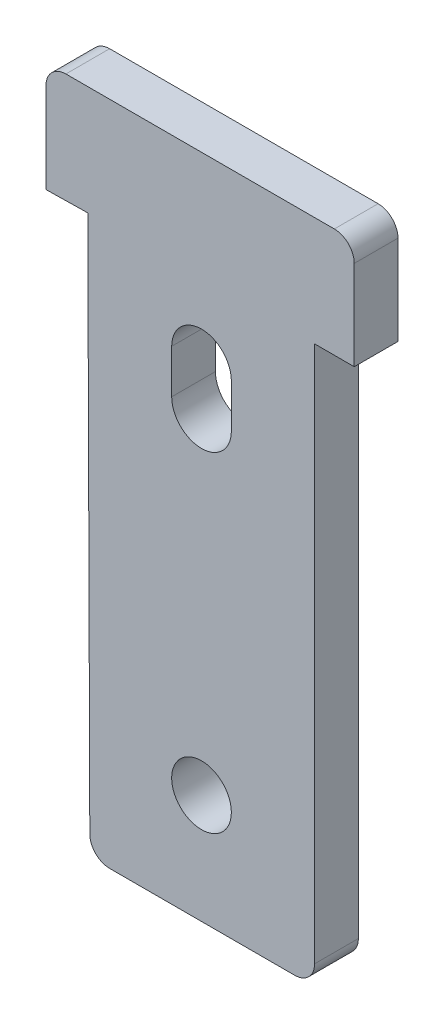
SolidWorks part; units mm, degrees
ref_plane "Front Plane" through (0, 0, 0) normal (0, 0, 1) x (1, 0, 0)
ref_plane "Top Plane" through (0, 0, 0) normal (0, 1, 0) x (1, 0, 0)
ref_plane "Right Plane" through (0, 0, 0) normal (1, 0, 0) x (0, 0, -1)
sketch "Sketch1" plane through (0, 0, 0) normal (0, 0, 1) x (1, 0, 0)
  line L12 (-4.5474, -16.75) -> (4.7563, -16.75)
  line L14 (-7.75, 11.2136) -> (-7.75, 15.75)
  line L17 (0.0702, -16.4445) -> (0.0702, 24.1035) construction
  line L19 (6.75, 16.75) -> (-6.75, 16.75)
  line L24 (0.0702, 5.35) -> (0.0702, 7.55) construction
  line L25 (-1.4298, 5.35) -> (-1.4298, 7.55)
  line L26 (-7.75, 11.2136) -> (-5.65, 11.25)
  line L27 (-5.65, 11.25) -> (-5.5474, -15.7538)
  line L28 (5.7563, -15.75) -> (5.7563, 11.25)
  line L29 (5.7563, 11.25) -> (7.75, 11.25)
  line L30 (7.75, 11.25) -> (7.75, 15.75)
  line L31 (1.5702, 5.35) -> (1.5702, 7.55)
  arc A0 (6.75, 16.75) -> (7.75, 15.75) centre (6.75, 15.75) cw
  arc A1 (-6.75, 16.75) -> (-7.75, 15.75) centre (-6.75, 15.75) ccw
  arc A2 (-4.5474, -16.75) -> (-5.5474, -15.7538) centre (-4.5474, -15.75) cw
  arc A3 (5.7563, -15.75) -> (4.7563, -16.75) centre (4.7563, -15.75) cw
  circle A4 centre (0.0702, -11.25) radius 1.5
  arc A5 (-1.4298, 5.35) -> (1.5702, 5.35) centre (0.0702, 5.35) ccw
  arc A6 (1.5702, 7.55) -> (-1.4298, 7.55) centre (0.0702, 7.55) ccw
  point P0 (0, 0)
  point P1 (0, 0)
  point P9 (0, 0)
  point P14 (7.75, 16.75)
  point P20 (-7.75, 16.75)
  point P23 (-5.5437, -16.75)
  point P26 (5.7563, -16.75)
  point P32 (0.0702, 6.45)
  dimension "D4" = 1
  dimension "D5" = 1
  dimension "D6" = 1
  dimension "D7" = 1
  dimension "D9" = 33.5
  dimension "D11" = 3
  dimension "D1" = 15.5
  dimension "D2" = 5.5
  dimension "D3" = 11.3
  dimension "D10" = 5.5
extrude "Boss-Extrude1" add sketch "Sketch1" along normal blind 2.2
